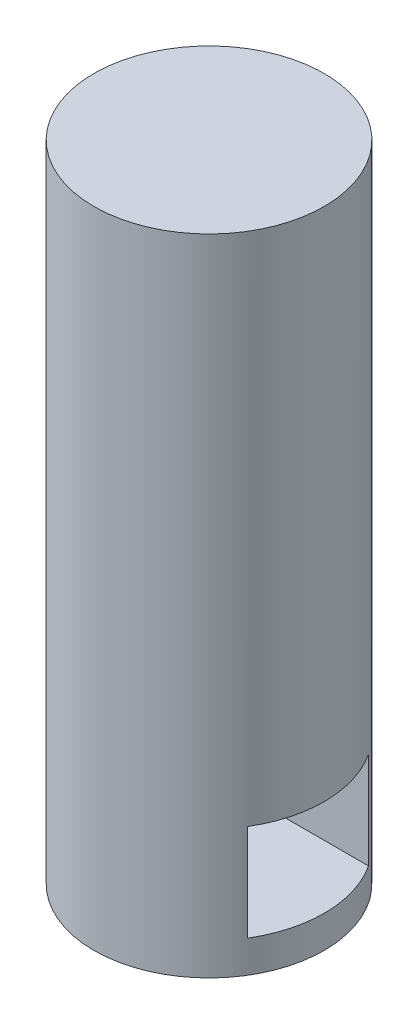
SolidWorks part; units mm, degrees
ref_plane "Front Plane" through (0, 0, 0) normal (0, 0, 1) x (1, 0, 0)
ref_plane "Top Plane" through (0, 0, 0) normal (0, 1, 0) x (1, 0, 0)
ref_plane "Right Plane" through (0, 0, 0) normal (1, 0, 0) x (0, 0, -1)
sketch "Sketch1" plane through (0, 0, 0) normal (0, 1, 0) x (1, 0, 0)
  circle A0 centre (0, 0) radius 7.15
extrude "Boss-Extrude1" add sketch "Sketch1" along normal blind 40
sketch "Sketch2" plane through (0, 0, 0) normal (0, -1, 0) x (1, 0, 0)
  circle A0 centre (0, 0) radius 1
extrude "Cut-Extrude1" cut sketch "Sketch2" against normal blind 4
ref_plane "Plane1" through (0, 2, 0) normal (0, 1, 0) x (1, 0, 0)
sketch "Sketch3" plane through (0, 2, 0) normal (0, 1, 0) x (1, 0, 0)
  line L1 (-7.5477, 3.9185) -> (7.3941, 3.9185)
  line L2 (-7.5477, 3.9185) -> (-7.5477, -3.7241)
  line L3 (-7.5477, -3.7241) -> (7.3941, -3.7241)
  line L4 (7.3941, 3.9185) -> (7.3941, -3.7241)
  point P2 (7.3941, 3.9185)
extrude "Cut-Extrude2" cut sketch "Sketch3" along normal blind 6
sketch "Sketch4" plane through (0, -2, 0) normal (0, -1, 0) x (1, 0, 0)
  circle A0 centre (0, 0) radius 1 construction
  circle A1 centre (0, 0) radius 1
